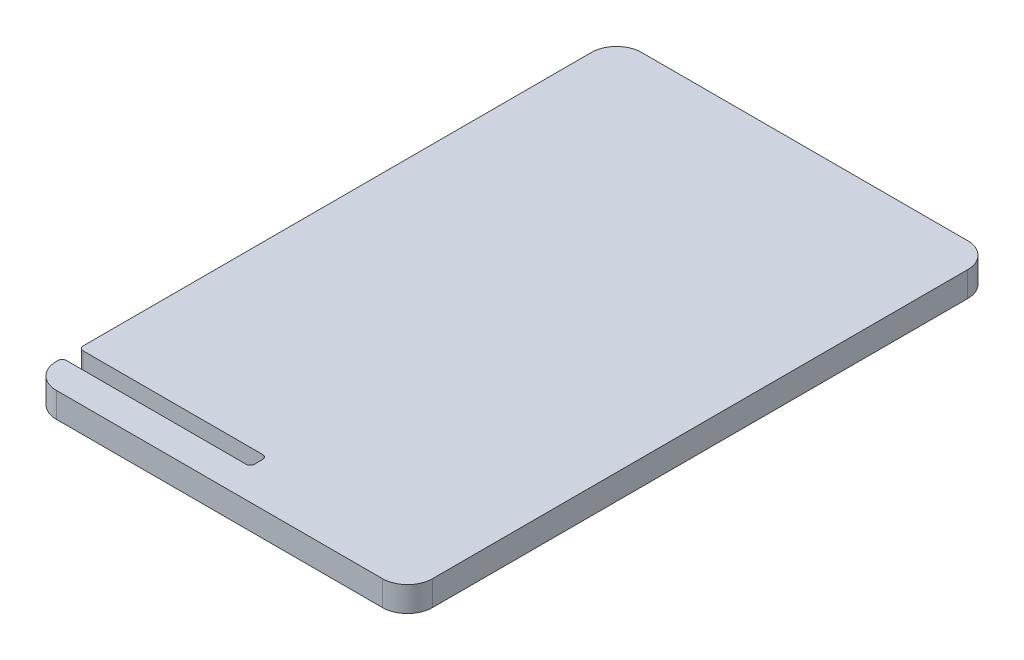
SolidWorks part; units mm, degrees
ref_plane "Alzado" through (0, 0, 0) normal (0, 0, 1) x (1, 0, 0)
ref_plane "Planta" through (0, 0, 0) normal (0, 1, 0) x (1, 0, 0)
ref_plane "Vista lateral" through (0, 0, 0) normal (1, 0, 0) x (0, 0, -1)
sketch "Croquis1" plane through (0, 0, 0) normal (0, 1, 0) x (1, 0, 0)
  line L1 (-22.5, 35.3062) -> (22.5, 35.3062)
  line L2 (-22.5, 35.3062) -> (-22.5, -34.6938)
  line L3 (-22.5, -34.6938) -> (22.5, -34.6938)
  line L4 (22.5, 35.3062) -> (22.5, -34.6938)
  dimension "D1" = 22.5
  dimension "D2" = 45
  dimension "D3" = 35.3062
  dimension "D4" = 70
extrude "Saliente-Extruir1" add sketch "Croquis1" along normal blind 3
sketch "Croquis2" plane through (0, 3, 0) normal (0, 1, 0) x (1, 0, 0)
  line L0 (-22.5, 35.3062) -> (-22.5, -34.6938) construction
  line L1 (-22.5, -29) -> (0, -29)
  line L2 (-22.5, -29) -> (-22.5, -31)
  line L3 (-22.5, -31) -> (0, -31)
  line L4 (0, -29) -> (0, -31)
  dimension "D1" = 2
  dimension "D2" = 31
  dimension "D3" = 22.5
extrude "Cortar-Extruir1" cut sketch "Croquis2" against normal up to surface (3 mm away) up to face at (0, 0, -0.3062)
fillet "Redondeo1" radius 3 4 edges at (-22.5, 1.5, 34.6938) (22.5, 1.5, 34.6938) (-22.5, 1.5, -35.3062) (22.5, 1.5, -35.3062)
fillet "Redondeo2" radius 0.5 4 edges at (-22.5, 1.5, 31) (0, 1.5, 31) (0, 1.5, 29) (-22.5, 1.5, 29)
